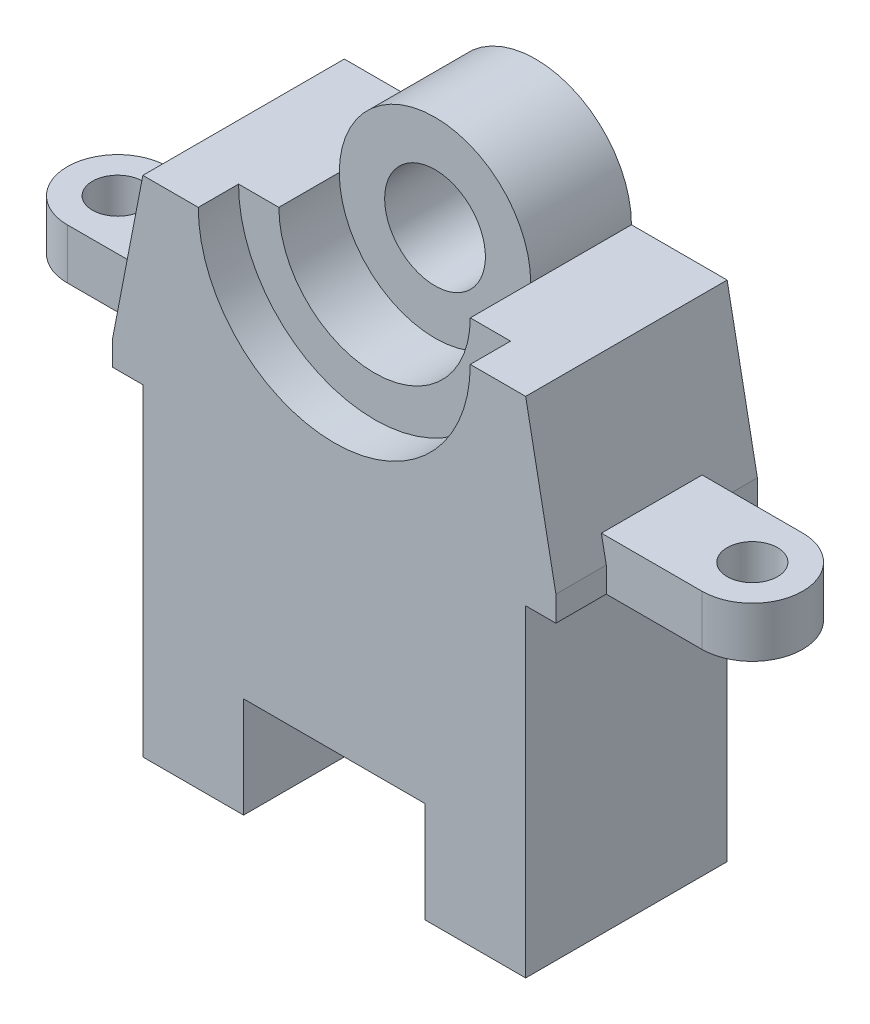
SolidWorks part; units mm, degrees
ref_plane "Front Plane" through (0, 0, 0) normal (0, 0, 1) x (1, 0, 0)
ref_plane "Top Plane" through (0, 0, 0) normal (0, 1, 0) x (1, 0, 0)
ref_plane "Right Plane" through (0, 0, 0) normal (1, 0, 0) x (0, 0, -1)
sketch "Sketch1" plane through (0, 0, 0) normal (0, 0, 1) x (1, 0, 0)
  line L0 (0, 0) -> (20, 0)
  line L1 (20, 0) -> (20, 20)
  line L2 (20, 20) -> (56, 20)
  line L3 (56, 20) -> (56, 0)
  line L4 (56, 0) -> (76, 0)
  line L5 (76, 0) -> (76, 64)
  line L6 (76, 64) -> (82, 64)
  line L7 (82, 64) -> (82, 69)
  line L8 (82, 69) -> (76, 100)
  line L9 (76, 100) -> (0, 100)
  line L10 (0, 100) -> (-6, 69)
  line L11 (-6, 69) -> (-6, 64)
  line L12 (-6, 64) -> (0, 64)
  line L13 (0, 64) -> (0, 0)
  point P3 (81.2425, 64)
  point P16 (59.0856, 100)
  point P17 (25.8501, 100)
  point P18 (0, 0)
  point P19 (0, 0)
  point P20 (0, 0)
  dimension "D1" = 36
  dimension "D2" = 76
  dimension "D3" = 20
  dimension "D4" = 64
  dimension "D5" = 36
  dimension "D6" = 88
  dimension "D7" = 64
  dimension "D8" = 5
  dimension "D9" = 5
extrude "Boss-Extrude1" add sketch "Sketch1" along normal blind 40
sketch "Sketch2" plane through (0, 0, 40) normal (0, 0, 1) x (1, 0, 0)
  line L0 (76, 100) -> (0, 100) construction
  line L1 (11, 100) -> (65, 100)
  arc A0 (11, 100) -> (65, 100) centre (38, 100) ccw
  dimension "D1" = 27
  dimension "D2" = 38
extrude "Cut-Extrude1" cut sketch "Sketch2" against normal blind 8
sketch "Sketch4" plane through (0, 0, 32) normal (0, 0, 1) x (1, 0, 0)
  line L0 (65, 100) -> (11, 100) construction
  line L1 (19, 100) -> (57, 100)
  line L2 (0, 64) -> (0, 0) construction
  line L3 (11, 100) -> (0, 100) construction
  arc A0 (19, 100) -> (57, 100) centre (38, 100) ccw
  point P7 (0, 0)
  dimension "D1" = 19
  dimension "D2" = 38
extrude "Cut-Extrude2" cut sketch "Sketch4" against normal through all
sketch "Sketch5" plane through (0, 0, 0) normal (0, 0, -1) x (-1, 0, 0)
  line L0 (-76, 0) -> (-76, 64) construction
  line L1 (-76, 100) -> (-57, 100) construction
  circle A0 centre (-38, 100) radius 19
  circle A1 centre (-38, 100) radius 10
  point P3 (0, 0)
  point P6 (0, 0)
  dimension "D1" = 38
  dimension "D2" = 20
  dimension "D3" = 38
extrude "Boss-Extrude2" add sketch "Sketch5" against normal blind 20
sketch "Sketch6" plane through (0, 64, 0) normal (0, -1, 0) x (1, 0, 0)
  line L0 (-3.171, 30) -> (-3.171, 10)
  line L1 (-3.171, 10) -> (-25, 10)
  line L2 (-3.171, 30) -> (-25, 30)
  line L3 (-6, 40) -> (-6, 0) construction
  line L4 (0, 0) -> (20, 0) construction
  arc A0 (-25, 30) -> (-25, 10) centre (-25, 20) ccw
  circle A1 centre (-25, 20) radius 5
  dimension "D1" = 10
  dimension "D2" = 10
  dimension "D3" = 19
  dimension "D4" = 20
extrude "Boss-Extrude3" add sketch "Sketch6" against normal blind 10
sketch "Sketch7" plane through (0, 64, 0) normal (0, -1, 0) x (1, 0, 0)
  line L0 (78.9535, 30) -> (78.9535, 10)
  line L1 (78.9535, 10) -> (101, 10)
  line L2 (78.9535, 30) -> (101, 30)
  line L3 (56, 0) -> (76, 0) construction
  line L4 (82, 40) -> (82, 0) construction
  arc A0 (101, 30) -> (101, 10) centre (101, 20) cw
  circle A1 centre (101, 20) radius 5
  point P6 (99.8867, 30.5265)
  point P7 (0, 0)
  point P8 (0, 0)
  point P9 (104.781, 9.3849)
  dimension "D1" = 10
  dimension "D2" = 10
  dimension "D3" = 20
  dimension "D4" = 19
extrude "Boss-Extrude4" add sketch "Sketch7" against normal blind 10
